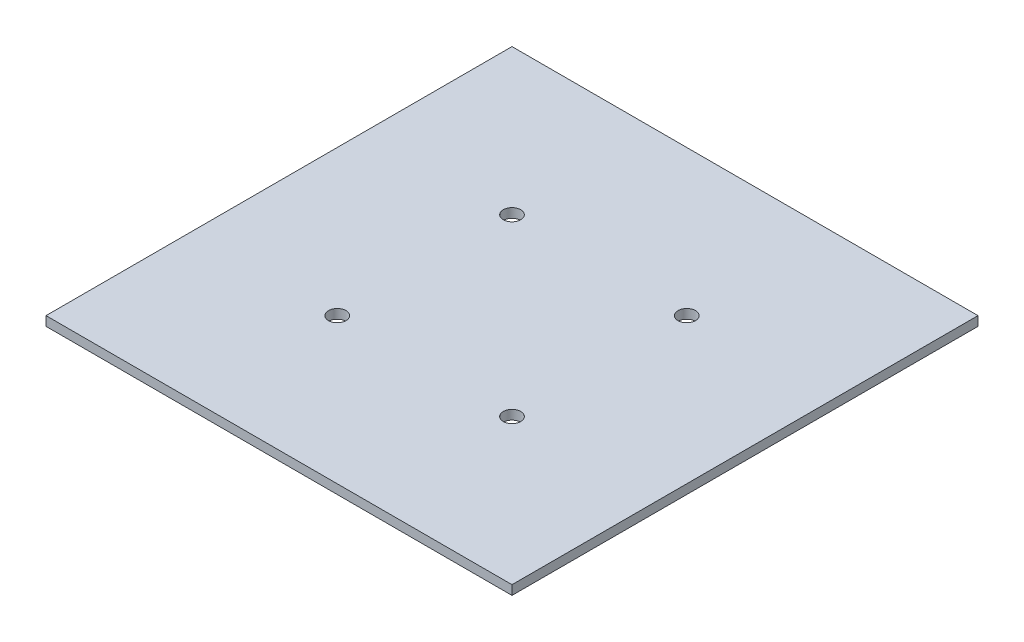
SolidWorks part; units mm, degrees
ref_plane "Plan de face" through (0, 0, 0) normal (0, 0, 1) x (1, 0, 0)
ref_plane "Plan de dessus" through (0, 0, 0) normal (0, 1, 0) x (1, 0, 0)
ref_plane "Plan de droite" through (0, 0, 0) normal (1, 0, 0) x (0, 0, -1)
sketch "Esquisse1" plane through (0, 0, 0) normal (0, 1, 0) x (1, 0, 0)
  line L0 (0, 40) -> (0, 0) construction
  line L1 (-40, 40) -> (40, 40)
  line L2 (-40, 40) -> (-40, -40)
  line L3 (-40, -40) -> (40, -40)
  line L4 (40, 40) -> (40, -40)
  line L5 (0, 0) -> (40, 0) construction
  circle A0 centre (15, 15) radius 1.5
  circle A1 centre (-15, 15) radius 1.5
  circle A2 centre (15, -15) radius 1.5
  circle A3 centre (-15, -15) radius 1.5
  dimension "D3" = 3
  dimension "D1" = 80
  dimension "D2" = 80
  dimension "D4" = 15
  dimension "D5" = 15
extrude "Extrusion1" add sketch "Esquisse1" along normal blind 1.6
